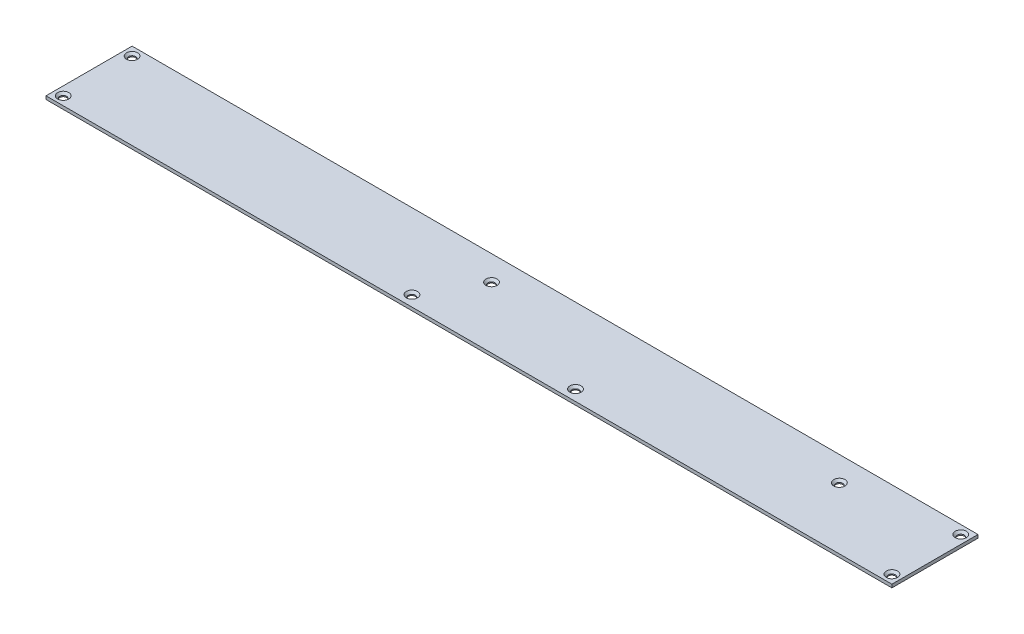
SolidWorks part; units mm, degrees
ref_plane "Ebene vorne" through (0, 0, 0) normal (0, 0, 1) x (1, 0, 0)
ref_plane "Ebene oben" through (0, 0, 0) normal (0, 1, 0) x (1, 0, 0)
ref_plane "Ebene rechts" through (0, 0, 0) normal (1, 0, 0) x (0, 0, -1)
sketch "Skizze1" plane through (0, 0, 0) normal (0, 1, 0) x (1, 0, 0)
  line L1 (-196.5, 20) -> (196.5, 20)
  line L2 (-196.5, 20) -> (-196.5, -20)
  line L3 (-196.5, -20) -> (196.5, -20)
  line L4 (196.5, 20) -> (196.5, -20)
  line L5 (-196.5, 20) -> (196.5, -20) construction
  line L6 (-196.5, -20) -> (196.5, 20) construction
  point P0 (0, 0)
extrude "Aufsatz-Linear austragen1" add sketch "Skizze1" along normal blind 1.5
sketch "Skizze2" plane through (0, 1.5, 0) normal (0, 1, 0) x (1, 0, 0)
  line L0 (196.5, -23) -> (-196.5, -23) construction
  line L5 (196.5, 20) -> (-196.5, 20) construction
  line L6 (196.5, -20) -> (196.5, 20) construction
  line L7 (196.5, 0) -> (-196.5, 0)
  line L8 (-196.5, 20) -> (-196.5, -20) construction
  line L9 (0, 20) -> (0, -20)
  line L10 (-196.5, -20) -> (196.5, -20) construction
  line L11 (143.5, 11) -> (143.4999, 6.18)
  line L12 (146, 11) -> (141, 11) construction
  line L13 (-18, 11) -> (-18, 6)
  line L14 (-20.5, 11) -> (-15.5, 11) construction
  circle A0 centre (192.5, 16) radius 1.6
  circle A1 centre (192.5, -16) radius 1.6
  circle A2 centre (-192.5, -16) radius 1.6
  circle A3 centre (-192.5, 16) radius 1.6
  circle A4 centre (44.5, -15) radius 1.6
  circle A5 centre (-31.5, -15) radius 1.6
  circle A6 centre (-18, 8.5) radius 1.6
  circle A7 centre (143.5, 8.59) radius 1.6
  dimension "D1" = 4
  dimension "D3" = 8
  dimension "D2" = 4
  dimension "D4" = 8
  dimension "D5" = 76
  dimension "D6" = 44.5
extrude "Schnitt-Linear austragen1" cut sketch "Skizze2" against normal through all contours A3 | A2 | A1 | A0 | A4 | L13 A6 | L13 A6 | L11 A7 | L11 A7 | A5
chamfer "Fase1" distance 1 angle 45 8 edges at (192.5, 1.5, -14.4) (192.5, 1.5, 17.6) (44.5, 1.5, 16.6) (-192.5, 1.5, 17.6) (-192.5, 1.5, -14.4) (-31.5, 1.5, 16.6) (-18, 1.5, -6.9) (143.5, 1.5, -6.99)
